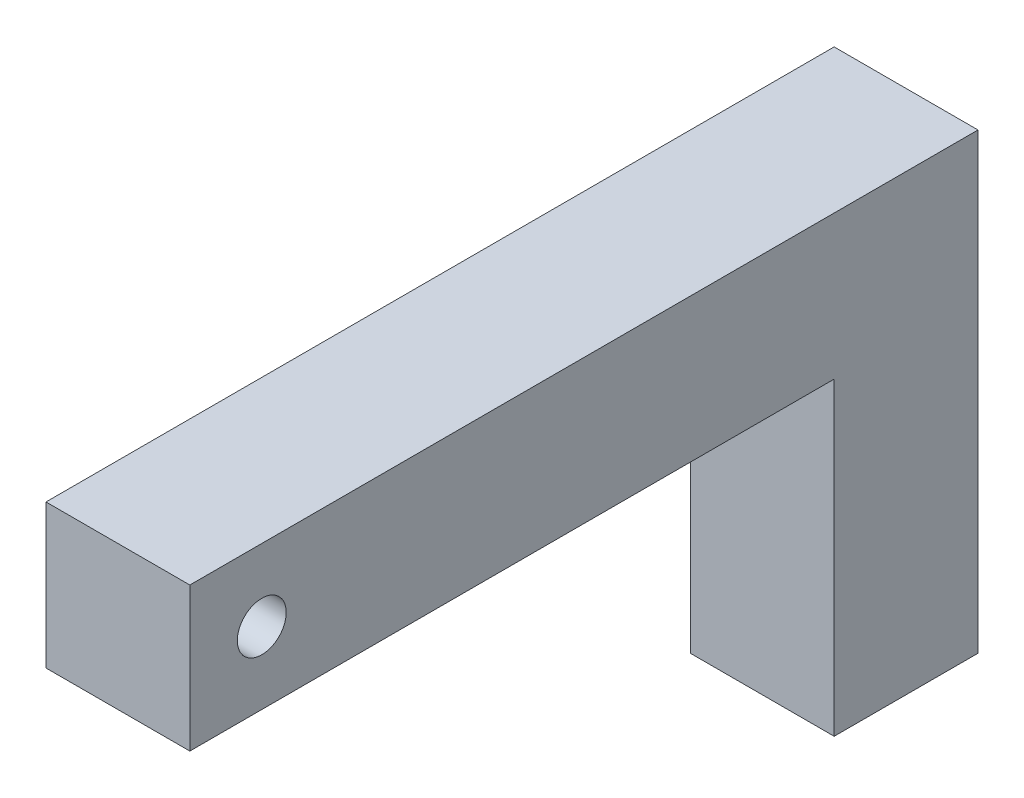
SolidWorks part; units mm, degrees
ref_plane "Front Plane" through (0, 0, 0) normal (0, 0, 1) x (1, 0, 0)
ref_plane "Top Plane" through (0, 0, 0) normal (0, 1, 0) x (1, 0, 0)
ref_plane "Right Plane" through (0, 0, 0) normal (1, 0, 0) x (0, 0, -1)
sketch "Sketch1" plane through (0, 0, 0) normal (1, 0, 0) x (0, 0, -1)
  line L0 (0, 0) -> (0, 10)
  line L1 (0, 10) -> (54.7945, 10)
  line L2 (54.7945, 10) -> (54.7945, -21.5068)
  line L3 (0, 0) -> (44.7945, 0)
  line L4 (44.7945, 0) -> (44.7945, -21.5068)
  line L5 (44.7945, -21.5068) -> (54.7945, -21.5068)
  circle A0 centre (5, 5) radius 1.7
  dimension "D3" = 5
  dimension "D1" = 10
  dimension "D2" = 10
extrude "Boss-Extrude1" add sketch "Sketch1" along normal blind 10
